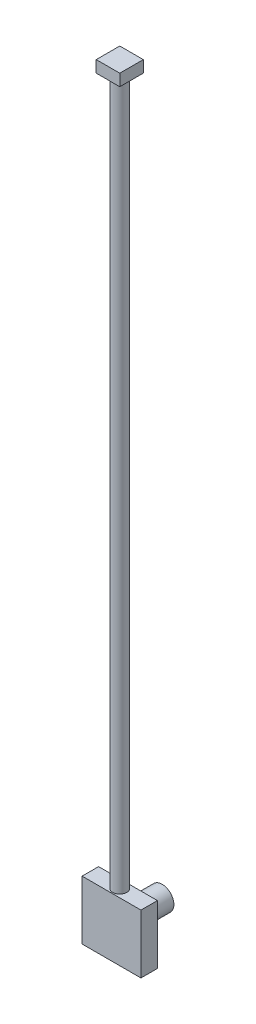
SolidWorks part; units mm, degrees
ref_plane "Спереди" through (0, 0, 0) normal (0, 0, 1) x (1, 0, 0)
ref_plane "Сверху" through (0, 0, 0) normal (0, 1, 0) x (1, 0, 0)
ref_plane "Справа" through (0, 0, 0) normal (1, 0, 0) x (0, 0, -1)
sketch "Профіль опори" plane through (0, 0, 0) normal (0, 0, 1) x (1, 0, 0)
  line L1 (125, 125) -> (-125, 125)
  line L2 (-125, 125) -> (-125, -125)
  line L3 (-125, -125) -> (125, -125)
  line L4 (125, -125) -> (125, 125)
  circle A0 centre (0, 0) radius 125 construction
  dimension "Висота" = 250
extrude "Опора" add sketch "Профіль опори" along normal mid plane 70
sketch "Профіль тіла" plane through (0, 0, 0) normal (0, 1, 0) x (1, 0, 0)
  circle A0 centre (0, 0) radius 30
  dimension "Діаметр" = 60
extrude "Тіло" add sketch "Профіль тіла" along normal blind 3000 from surface at 125 starting at face at (0, 125, 0)
sketch "Профіль опори траверси" plane through (0, 3125, 0) normal (0, 1, 0) x (1, 0, 0)
  line L1 (50, 50) -> (-50, 50)
  line L2 (-50, 50) -> (-50, -50)
  line L3 (-50, -50) -> (50, -50)
  line L4 (50, -50) -> (50, 50)
  circle A0 centre (0, 0) radius 50 construction
  dimension "Ширина" = 100
extrude "Опора траверси" add sketch "Профіль опори траверси" along normal blind 50
sketch "Профіль осі траверси" plane through (0, 0, 0) normal (0, 0, 1) x (1, 0, 0)
  circle A0 centre (0, 0) radius 50
  dimension "Діаметр" = 100
extrude "Вісь опори" add sketch "Профіль осі траверси" against normal blind 180
equation "\"Довжина@Тіло\" = 3000.0"
equation "\"Ширина@Опора\" = 70.0"
